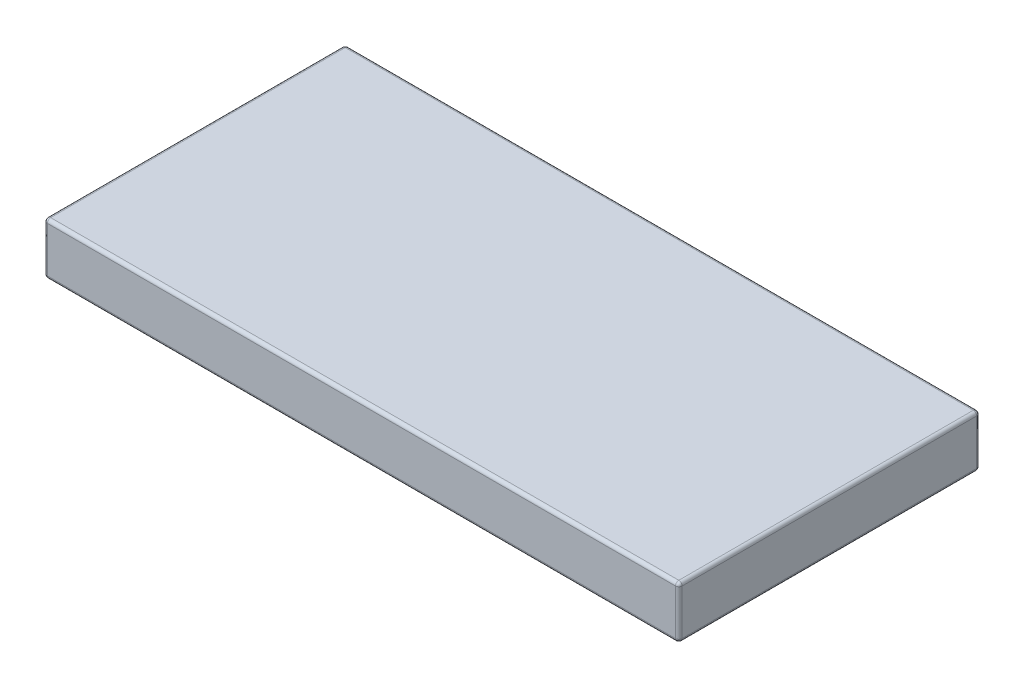
SolidWorks part; units mm, degrees
material "NdFeB"
ref_plane "Front Plane" through (0, 0, 0) normal (0, 0, 1) x (1, 0, 0)
ref_plane "Top Plane" through (0, 0, 0) normal (0, 1, 0) x (1, 0, 0)
ref_plane "Right Plane" through (0, 0, 0) normal (1, 0, 0) x (0, 0, -1)
sketch "Sketch1" plane through (0, 0, 0) normal (0, 1, 0) x (1, 0, 0)
  line L1 (-9.57, -4.54) -> (9.57, -4.54)
  line L2 (-9.57, -4.54) -> (-9.57, 4.54)
  line L3 (-9.57, 4.54) -> (9.57, 4.54)
  line L4 (9.57, -4.54) -> (9.57, 4.54)
  line L5 (-9.57, -4.54) -> (9.57, 4.54) construction
  line L6 (-9.57, 4.54) -> (9.57, -4.54) construction
  point P0 (0, 0)
  dimension "D1" = 19.14
  dimension "D2" = 9.08
extrude "Boss-Extrude1" add sketch "Sketch1" along normal blind 1.57
fillet "Fillet1" radius 0.1 12 edges at (0, 1.57, 4.54) (-9.57, 1.57, 0) (0, 1.57, -4.54) (9.57, 1.57, 0) (0, 0, -4.54) (-9.57, 0, 0) (0, 0, 4.54) (9.57, 0, 0) (-9.57, 0.785, 4.54) (-9.57, 0.785, -4.54) (9.57, 0.785, -4.54) (9.57, 0.785, 4.54)
equation "\"Magnet thickness\"= 1.57mm"
equation "\"Magnet short side\"= 9.08mm"
equation "\"Magnet long side\"= 19.14mm"
equation "\"D1@Sketch1\"=\"Magnet long side\""
equation "\"D2@Sketch1\"=\"Magnet short side\""
equation "\"D1@Boss-Extrude1\"=\"Magnet thickness\""
